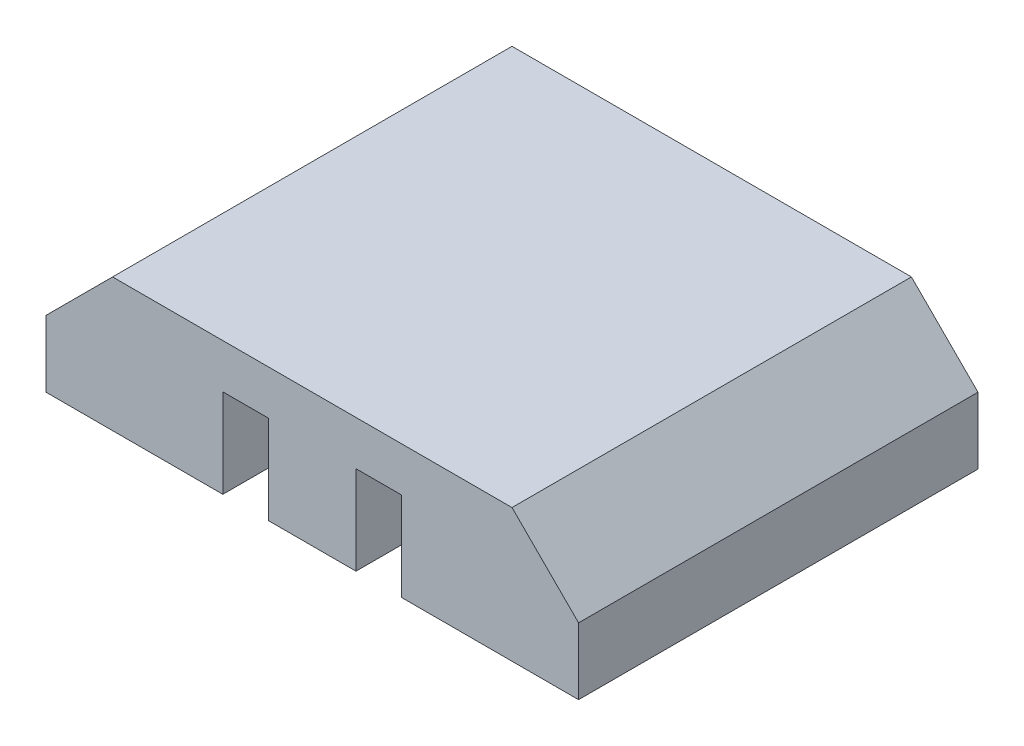
SolidWorks part; units mm, degrees
ref_plane "Front Plane" through (0, 0, 0) normal (0, 0, 1) x (1, 0, 0)
ref_plane "Top Plane" through (0, 0, 0) normal (0, 1, 0) x (1, 0, 0)
ref_plane "Right Plane" through (0, 0, 0) normal (1, 0, 0) x (0, 0, -1)
sketch "Sketch1" plane through (0, 0, 0) normal (0, 1, 0) x (1, 0, 0)
  line L0 (50, 14) -> (50, 85)
  line L1 (30, 14) -> (50, 14)
  line L2 (30, 85) -> (30, 14)
  line L3 (50, 85) -> (30, 85)
  line L4 (50, 95) -> (50, 166)
  line L5 (30, 95) -> (50, 95)
  line L6 (30, 166) -> (30, 95)
  line L7 (50, 166) -> (30, 166)
  line L8 (20, 176) -> (20, 4)
  line L9 (20, 4) -> (0, 4)
  line L10 (0, 4) -> (0, 0)
  line L11 (0, 0) -> (80, 0)
  line L12 (80, 0) -> (80, 4)
  line L13 (80, 4) -> (60, 4)
  line L14 (60, 4) -> (60, 176)
  line L15 (60, 176) -> (80, 176)
  line L16 (80, 176) -> (80, 180)
  line L17 (80, 180) -> (0, 180)
  line L18 (0, 180) -> (0, 176)
  line L19 (0, 176) -> (20, 176)
sketch "Sketch2" plane through (0, 0, 0) normal (0, 1, 0) x (1, 0, 0)
  line L3 (30.15, 135) -> (49.85, 135)
  line L8 (30.15, 45) -> (49.85, 45)
  line L11 (60.15, 135) -> (100, 135)
  line L13 (60.15, 45) -> (100, 45)
  line L14 (100, 135) -> (100, 45)
  line L16 (19.85, 135) -> (-20, 135)
  line L18 (19.85, 45) -> (-20, 45)
  line L19 (-20, 135) -> (-20, 45)
  line L20 (30.15, 95.15) -> (30.15, 134.85)
  line L21 (19.85, 135) -> (19.85, 45)
  line L22 (60.15, 135) -> (60.15, 45)
  line L24 (49.85, 95.15) -> (49.85, 134.85)
  line L25 (30.15, 95.15) -> (49.85, 95.15)
  line L26 (30, 135) -> (50, 135) construction
  line L28 (30.15, 134.85) -> (30.15, 135)
  line L29 (30.15, 135) -> (49.85, 135)
  line L30 (49.85, 134.85) -> (49.85, 135)
  line L31 (30.15, 134.85) -> (49.85, 134.85) construction
  line L32 (30, 95) -> (30, 135) construction
  line L33 (50, 95) -> (50, 135) construction
  line L34 (30, 95) -> (50, 95) construction
  line L35 (30.15, 84.85) -> (30.15, 45.15)
  line L37 (49.85, 84.85) -> (49.85, 45.15)
  line L38 (30.15, 84.85) -> (49.85, 84.85)
  line L39 (30, 45) -> (50, 45) construction
  line L41 (30.15, 45.15) -> (30.15, 45)
  line L42 (30.15, 45) -> (49.85, 45)
  line L43 (49.85, 45.15) -> (49.85, 45)
  line L44 (30.15, 45.15) -> (49.85, 45.15) construction
  line L45 (30, 85) -> (30, 45) construction
  line L46 (50, 85) -> (50, 45) construction
  line L47 (30, 85) -> (50, 85) construction
  dimension "D1" = 0.15
  dimension "D2" = 0.15
extrude "Boss-Extrude1" add sketch "Sketch2" along normal blind 20 contours L21 L16 L19 L18 | L24 L30 L3 L28 L20 L25 | L43 L37 L38 L35 L41 L8 | L11 L22 L13 L14
sketch "Sketch3" plane through (0, 20, 0) normal (0, 1, 0) x (1, 0, 0)
  line L1 (100, 45) -> (-20, 45)
  line L2 (100, 45) -> (100, 135)
  line L3 (100, 135) -> (-20, 135)
  line L4 (-20, 45) -> (-20, 135)
extrude "Boss-Extrude2" add sketch "Sketch3" along normal blind 10
sketch "Sketch5" plane through (0, 0, -45) normal (0, 0, 1) x (1, 0, 0)
  line L0 (-20, 30) -> (-20, 15)
  line L1 (-20, 30) -> (-20, 0) construction
  line L2 (-20, 30) -> (-5, 30)
  line L3 (-20, 30) -> (100, 30) construction
  line L4 (-5, 30) -> (-20, 15)
  line L5 (100, 30) -> (85, 30)
  line L6 (100, 30) -> (100, 15)
  line L7 (100, 15) -> (85, 30)
extrude "Cut-Extrude2" cut sketch "Sketch5" against normal blind 114 contours L4 L0 L2 | L7 L5 L6
